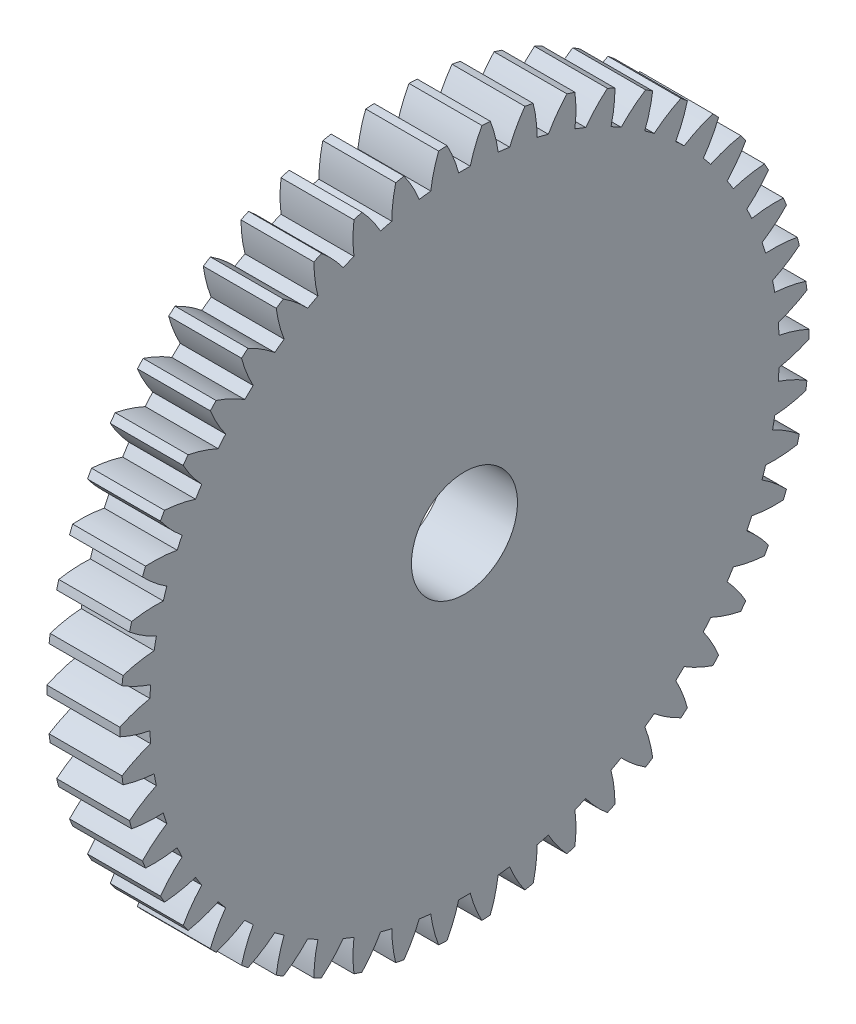
SolidWorks part; units mm, degrees
material "ﾎﾟﾘｵｷｼﾒﾁﾚﾝ(POM)ｱｾﾀｰﾙ共重合体"
ref_plane "Plane1" through (0, 0, 0) normal (0, 0, 1) x (1, 0, 0)
ref_plane "Plane2" through (0, 0, 0) normal (0, 1, 0) x (1, 0, 0)
ref_plane "Plane3" through (0, 0, 0) normal (1, 0, 0) x (0, 0, -1)
other "Configuration Table"
sketch "HoldingSke" plane through (0, 0, 0) normal (0, 1, 0) x (1, 0, 0)
  line L0 (0, 0) -> (0.6428, -0.766)
  line L1 (-15, 0) -> (100, 0) construction
  line L2 (0, 0) -> (-2.1039, 2.3779)
  line L3 (0, 0) -> (-11.863, 4.5341)
  line L4 (0, 0) -> (5.5511, 6.6156)
  line L5 (0, 0) -> (-46.8476, -17.4728)
  line L6 (0, 0) -> (-4.5593, -3.0762)
  line L7 (-2.1039, 2.3779) -> (8.6586, 51.2059)
  line L8 (-76.2, 54.61) -> (-75.2, 54.61)
  line L9 (-71.009, 38.7566) -> (-53.1078, 45.2721)
  line L10 (-76.2, 71.12) -> (104.1128, 71.12)
  line L11 (0, 0) -> (-5.5, 0)
  line L12 (-76.2, 101.6) -> (-76.162, 101.6)
  line L13 (24.9733, 27.94) -> (52.9518, 28.4284)
  line L14 (24.9733, 27.94) -> (24.9743, 27.94)
  line L15 (24.9733, 27.94) -> (100.4006, 29.5858)
  line L16 (-63.627, -1) -> (-12.827, -1)
  circle A0 centre (0, 0) radius 4
  circle A1 centre (0, 0) radius 23.749
  circle A2 centre (0, 0) radius 37.5
  circle A3 centre (0, 0) radius 4
  dimension "MHD" = 47.498
  dimension "Hub_dia" = 75
  dimension "Bore" = 8
  dimension "MBD" = 8
  dimension "Num_teeth" = 50
  dimension "Pitch" = 1
  dimension "Overall_len" = 50
  dimension "Show_teeth" = 50
  dimension "Thickness" = 5.5
  dimension "OAL" = 50.0001
  dimension "T_dim" = 1
  dimension "Ap" = 20
  dimension "H" = 19.05
  dimension "Pitch_radius" = 180.3128
  dimension "Width" = 5.5
  dimension "Backlash" = 0.038
  dimension "Addendum_fac" = 1
  dimension "Dedendum_fac" = 1.25
  dimension "Clearance_fac" = 0.25
  dimension "Dedendum_add" = 0.001
  dimension "Module" = 1
sketch "BasProSke" plane through (0, 0, 0) normal (0, 1, 0) x (1, 0, 0)
  line L0 (-10, 0) -> (60, 0) construction
  line L1 (0, 0) -> (0, 26)
  line L2 (0, 0) -> (5.5, 0)
  line L3 (5.5, 0) -> (5.5, 26)
  line L4 (5.5, 26) -> (0, 26)
  dimension "Thickness" = 5.5
  dimension "Diameter" = 52
revolve "Base-Revolve" add sketch "BasProSke" angle 360 about L0
sketch "TooCutSke" plane through (0, 0, 0) normal (1, 0, 0) x (0, 0, -1)
  line L1 (0, 0) -> (0, 107) construction
  line L2 (0, 0) -> (-0.8518, 24.9855) construction
  line L3 (0, 0) -> (-3.1382, 49.8807) construction
  line L4 (-0.8518, 24.9855) -> (-1.5691, 24.9404) construction
  arc A0 (0.4377, 23.745) -> (-0.4377, 23.745) centre (0, 0) ccw
  arc A1 (1.3294, 25.9914) -> (-1.3294, 25.9914) centre (0, 0) ccw
  circle A2 centre (0, 0) radius 25 construction
  circle A3 centre (0, 0) radius 23.4923 construction
  arc A4 (-0.4377, 23.745) -> (-1.3294, 25.9914) centre (-10.1099, 21.2056) ccw
  arc A5 (1.3294, 25.9914) -> (0.4377, 23.745) centre (10.1099, 21.2056) ccw
  dimension "Root_dia" = 47.498
  dimension "Overcut_dia" = 52.0508
  dimension "Pitch_dia" = 50
  dimension "Base_dia" = 46.9846
  dimension "Flank_rad" = 10
  dimension "Half_ang" = 3.6
  dimension "Half_CT" = 0.7188
extrude "ToothCut" cut sketch "TooCutSke" along normal through all
fillet "Breaks" [suppressed] radius 0.02
fillet "RootFillets" [suppressed] radius 0.251
pattern_circular "TeethCuts" count 50 every 7.2 about axis through (-10, 0, 0) along (1, 0, 0) of "ToothCut", "RootFillets", "Breaks"
sketch "HubNeaOneSke" plane through (0, 0, 0) normal (-1, 0, 0) x (0, 0, 1)
  circle A0 centre (0, 0) radius 23.749
  dimension "Diameter" = 47.498
extrude "HubNearOne" [suppressed] add sketch "HubNeaOneSke" along normal blind 44.5001
sketch "HubNeaBotSke" plane through (0, 0, 0) normal (-1, 0, 0) x (0, 0, 1)
  circle A0 centre (0, 0) radius 23.749
  dimension "Diameter" = 47.498
extrude "HubNearBoth" [suppressed] add sketch "HubNeaBotSke" along normal blind 22.25
ref_plane "FarPln" through (5.5, 0, 0) normal (1, 0, 0) x (0, 0, -1)
sketch "HubFarSke" plane through (5.5, 0, 0) normal (1, 0, 0) x (0, 0, -1)
  circle A0 centre (0, 0) radius 23.749
  dimension "Diameter" = 47.498
extrude "HubFar" [suppressed] add sketch "HubFarSke" along normal blind 22.25
sketch "BorSke" plane through (0, 0, 0) normal (1, 0, 0) x (0, 0, -1)
  circle A0 centre (0, 0) radius 4
  dimension "Diameter" = 8
extrude "Bore" cut sketch "BorSke" along normal mid plane 100.0001
sketch "KeySke" plane through (0, 0, 0) normal (1, 0, 0) x (0, 0, -1)
  line L0 (-1, 0) -> (-1, 5)
  line L1 (-1, 5) -> (1, 5)
  line L2 (1, 5) -> (1, 0)
  line L3 (0, 0) -> (0, 34) construction
  line L4 (-1, 0) -> (1, 0)
  dimension "Offset" = 5
  dimension "Width" = 2
extrude "Keyway" [suppressed] cut sketch "KeySke" along normal mid plane 100.0001
pattern_circular "Keyway2" [suppressed] count 2 every 90 about axis through (-10, 0, 0) along (1, 0, 0)
equation "' \"Module@HoldingSke\" = 6.35"
equation "' \"Num_teeth@HoldingSke\" = 12"
equation "' \"Ap@HoldingSke\" =  20"
equation "' \"Ap@HoldingSke\" = 20"
equation "' \"Width@HoldingSke\" = 0.5 * 25.4"
equation "' \"Hub_dia@HoldingSke\"= 1 * 25.4"
equation "' \"Hub_dia@HoldingSke\" = 1 * 25.4"
equation "' \"Overall_len@HoldingSke\" = 1.0 * 25.4"
equation "' \"Bore@HoldingSke\" = 0.75 * 25.4"
equation "' \"T_dim@HoldingSke\" = 0.1 * 25.4"
equation "' \"Width@KeySke\" = 0.25 * 25.4"
equation "' \"Show_teeth@HoldingSke\" = 13"
equation "' \"Backlash@HoldingSke\" = 0.009 * 25.4"
equation "' \"Addendum_fac@HoldingSke\" = 1.0"
equation "' \"Dedendum_fac@HoldingSke\" = 1.25"
equation "' \"Dedendum_add@HoldingSke\" = 0.00005 * 25.4"
equation "' \"Clearance_fac@HoldingSke\" = 0.25"
equation "\"Pitch@HoldingSke\" = 1 / \"Module@HoldingSke\""
equation "\"Overcut_dia@TooCutSke\" = (\"Num_teeth@HoldingSke\" + 2 * \"Addendum_fac@HoldingSke\") / \"Pitch@HoldingSke\" + 0.002 * 25.4"
equation "\"Pitch_dia@TooCutSke\" = \"Num_teeth@HoldingSke\" / \"Pitch@HoldingSke\""
equation "\"Base_dia@TooCutSke\" = \"Num_teeth@HoldingSke\" / \"Pitch@HoldingSke\" * cos((\"Ap@HoldingSke\"  * 3.14159265 / 180))"
equation "\"Root_dia@TooCutSke\" = (\"Num_teeth@HoldingSke\" + 2) / \"Pitch@HoldingSke\" - 2 * (\"Addendum_fac@HoldingSke\" + \"Dedendum_fac@HoldingSke\") / \"Pitch@HoldingSke\" - \"Dedendum_add@HoldingSke\" * 2"
equation "\"Half_ang@TooCutSke\" = 180 / \"Num_teeth@HoldingSke\""
equation "\"Half_CT@TooCutSke\" = \"Num_teeth@HoldingSke\" / \"Pitch@HoldingSke\" * sin((3.14159265 / 2 / \"Num_teeth@HoldingSke\")) / 2 - 7 * \"Backlash@HoldingSke\" / 4"
equation "\"Flank_rad@TooCutSke\" = \"Num_teeth@HoldingSke\" / \"Pitch@HoldingSke\" / 5"
equation "\"Radius@RootFillets\" = \"Clearance_fac@HoldingSke\" / \"Pitch@HoldingSke\" + \"Dedendum_add@HoldingSke\""
equation "\"Break_rad@Breaks\" = 0.02 / \"Pitch@HoldingSke\""
equation "\"Thickness@HoldingSke\" = \"Width@HoldingSke\""
equation "\"OAL@HoldingSke\" = \"Thickness@HoldingSke\""
equation "\"MHD@HoldingSke\" = (\"Num_teeth@HoldingSke\" + 2) / \"Pitch@HoldingSke\" - 2 * (\"Addendum_fac@HoldingSke\" + \"Dedendum_fac@HoldingSke\")  / \"Pitch@HoldingSke\" - \"Dedendum_add@HoldingSke\" * 2"
equation "\"MBD@HoldingSke\" = (\"Num_teeth@HoldingSke\" + 2) / \"Pitch@HoldingSke\" - 2 * (\"Addendum_fac@HoldingSke\" + \"Dedendum_fac@HoldingSke\")  / \"Pitch@HoldingSke\" - \"Dedendum_add@HoldingSke\" * 2 - 0.002 * 25.4"
equation "\"MHD@HoldingSke\" = ((sgn( \"MHD@HoldingSke\" - \"Hub_dia@HoldingSke\" )-1)*( \"MHD@HoldingSke\" - \"Hub_dia@HoldingSke\" ))/-2+ \"Hub_dia@HoldingSke\""
equation "\"MBD@HoldingSke\" = ((sgn( \"MBD@HoldingSke\" - \"Bore@HoldingSke\" )-1)*( \"MBD@HoldingSke\" - \"Bore@HoldingSke\" ))/-2+ \"Bore@HoldingSke\""
equation "\"OAL@HoldingSke\" = ((sgn( \"OAL@HoldingSke\" - \"Overall_len@HoldingSke\" )+1)*( \"OAL@HoldingSke\" - \"Overall_len@HoldingSke\" ))/2 + \"Overall_len@HoldingSke\" + 0.000002 * 25.4"
equation "\"Num_teeth@TeethCuts\" = int( \"Show_teeth@HoldingSke\" ) + 1"
equation "\"Num_teeth@TeethCuts\" = ((sgn( \"Num_teeth@TeethCuts\" - \"Num_teeth@HoldingSke\" )-1)*( \"Num_teeth@TeethCuts\" - \"Num_teeth@HoldingSke\" ))/-2+ \"Num_teeth@HoldingSke\""
equation "\"Num_teeth@TeethCuts\" = ((sgn( \"Num_teeth@TeethCuts\" - 2.0)+1)*( \"Num_teeth@TeethCuts\" - 2.0))/2 +2.0"
equation "\"Angle@TeethCuts\" = 360.0 / \"Num_teeth@HoldingSke\""
equation "\"Diameter@BasProSke\" = (\"Num_teeth@HoldingSke\" + 2 * \"Addendum_fac@HoldingSke\") / \"Pitch@HoldingSke\""
equation "\"Thickness@BasProSke\"  = \"Thickness@HoldingSke\""
equation "' \"Fillet_rad@BasProSke\" =  \"Thickness@HoldingSke\" * 0.05"
equation "' \"Fillet_rad@BasProSke\" = \"Thickness@HoldingSke\" * 0.05"
equation "\"MHD@HoldingSke\" = ((sgn( \"MHD@HoldingSke\" - \"Root_dia@TooCutSke\" )-1)*( \"MHD@HoldingSke\" - \"Root_dia@TooCutSke\" ))/-2+ \"Root_dia@TooCutSke\""
equation "\"Diameter@HubNeaOneSke\" = \"MHD@HoldingSke\""
equation "\"Length@HubNearOne\" = \"OAL@HoldingSke\" - \"Thickness@BasProSke\""
equation "\"Diameter@HubNeaBotSke\" = \"MHD@HoldingSke\""
equation "\"Length@HubNearBoth\" = ( \"OAL@HoldingSke\" - \"Thickness@BasProSke\" ) / 2.0"
equation "\"Thickness@FarPln\" = \"Thickness@BasProSke\""
equation "\"Diameter@HubFarSke\" = \"MHD@HoldingSke\""
equation "\"Length@HubFar\" = ( \"OAL@HoldingSke\" - \"Thickness@BasProSke\" ) / 2.0"
equation "\"Diameter@BorSke\" = \"MBD@HoldingSke\""
equation "\"D1@Bore\" = \"OAL@HoldingSke\" * 2.0"
equation "\"D1@Keyway\" = \"OAL@HoldingSke\" * 2.0"
equation "\"Offset@KeySke\" = \"T_dim@HoldingSke\" + \"MBD@HoldingSke\" / 2.0"
